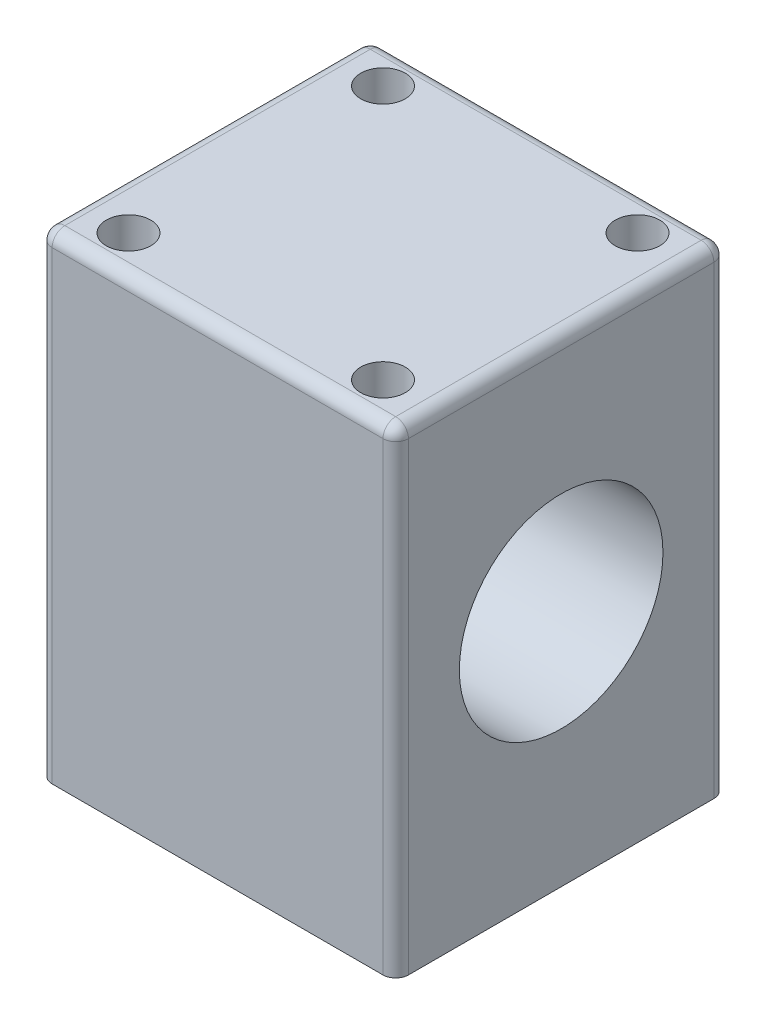
SolidWorks part; units mm, degrees
ref_plane "Front Plane" through (0, 0, 0) normal (0, 0, 1) x (1, 0, 0)
ref_plane "Top Plane" through (0, 0, 0) normal (0, 1, 0) x (1, 0, 0)
ref_plane "Right Plane" through (0, 0, 0) normal (1, 0, 0) x (0, 0, -1)
sketch "Sketch1" plane through (0, 0, 0) normal (1, 0, 0) x (0, 0, -1)
  line L1 (-13, -18.75) -> (13, -18.75)
  line L2 (-13, -18.75) -> (-13, 18.75)
  line L3 (-13, 18.75) -> (13, 18.75)
  line L4 (13, -18.75) -> (13, 18.75)
  line L5 (-13, -18.75) -> (13, 18.75) construction
  line L6 (-13, 18.75) -> (13, -18.75) construction
  circle A0 centre (0, 0) radius 8
  dimension "D1" = 16
  dimension "D2" = 37.5
  dimension "D3" = 26
extrude "Boss-Extrude1" add sketch "Sketch1" along normal mid plane 28
sketch "Sketch2" plane through (0, 18.75, 0) normal (0, 1, 0) x (1, 0, 0)
  line L1 (10, -10) -> (-10, -10) construction
  line L2 (10, -10) -> (10, 10) construction
  line L3 (10, 10) -> (-10, 10) construction
  line L4 (-10, -10) -> (-10, 10) construction
  line L5 (10, -10) -> (-10, 10) construction
  line L6 (10, 10) -> (-10, -10) construction
  circle A0 centre (-10, 10) radius 1.75
  circle A1 centre (10, 10) radius 1.75
  circle A2 centre (10, -10) radius 1.75
  circle A3 centre (-10, -10) radius 1.75
  point P0 (0, 0)
  dimension "D3" = 3.5
  dimension "D1" = 20
  dimension "D2" = 20
extrude "Cut-Extrude1" cut sketch "Sketch2" against normal blind 32
sketch "Sketch5" plane through (-14, 0, 0) normal (-1, 0, 0) x (0, 0, 1)
  circle A2 centre (0, 0) radius 6
  circle A4 centre (0, 0) radius 8.35
  dimension "D1" = 16.7
extrude "Boss-Extrude3" add sketch "Sketch5" against normal blind 3
fillet "Fillet3" radius 1 8 edges at (-14, 0, 13) (14, 0, 13) (-14, 0, -13) (-14, 18.75, 0) (0, 18.75, 13) (14, 0, -13) (0, 18.75, -13) (14, 18.75, 0)
